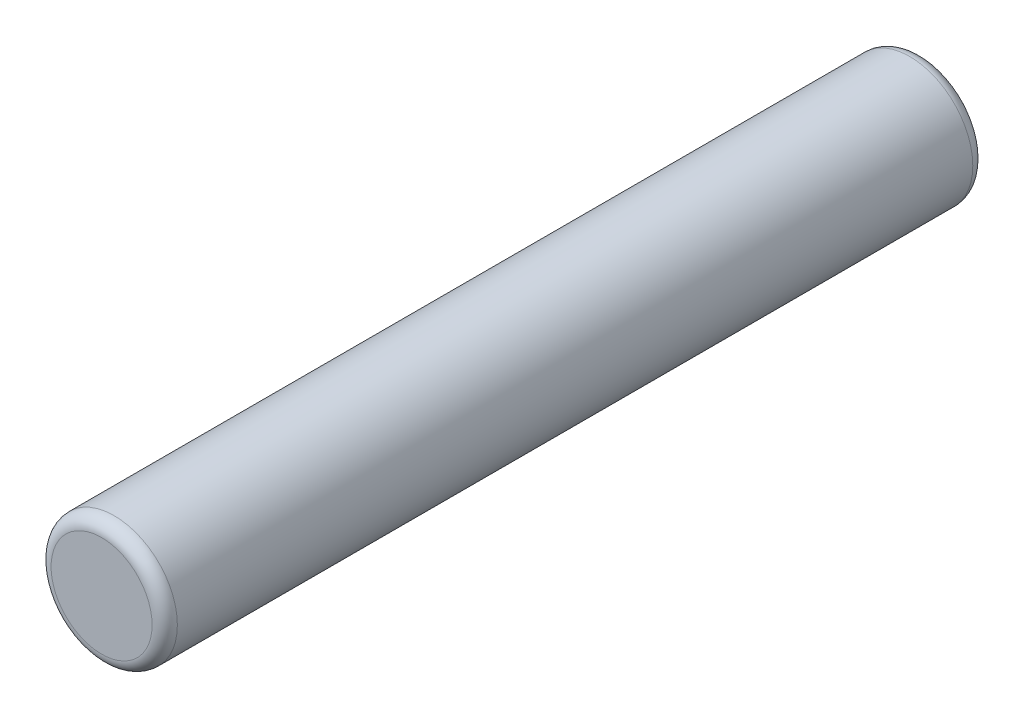
SolidWorks part; units mm, degrees
ref_plane "Plan de face" through (0, 0, 0) normal (0, 0, 1) x (1, 0, 0)
ref_plane "Plan de dessus" through (0, 0, 0) normal (0, 1, 0) x (1, 0, 0)
ref_plane "Plan de droite" through (0, 0, 0) normal (1, 0, 0) x (0, 0, -1)
sketch "Esquisse1" plane through (0, 0, 0) normal (0, 0, 1) x (1, 0, 0)
  circle A0 centre (0, 0) radius 10
  dimension "D1" = 20
extrude "Boss.-Extru.1" add sketch "Esquisse1" along normal blind 130
fillet "Congé1" radius 2 2 edges at (10, 0, 0) (10, 0, 130)
